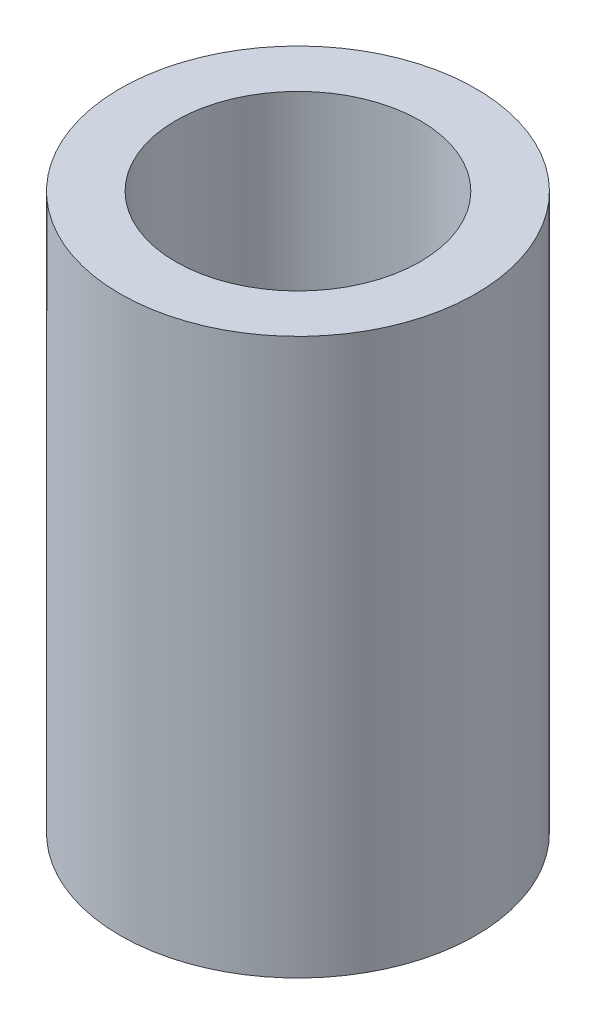
SolidWorks part; units mm, degrees
ref_plane "Płaszczyzna przednia" through (0, 0, 0) normal (0, 0, 1) x (1, 0, 0)
ref_plane "Płaszczyzna górna" through (0, 0, 0) normal (0, 1, 0) x (1, 0, 0)
ref_plane "Płaszczyzna prawa" through (0, 0, 0) normal (1, 0, 0) x (0, 0, -1)
sketch "Sketch1" plane through (0, 0, 0) normal (0, 1, 0) x (1, 0, 0)
  line L0 (-0.2998, -0.4611) -> (0.2998, 0.4611) construction
  line L1 (0.474, -0.9926) -> (-0.474, 0.9926) construction
  circle A0 centre (0, 0) radius 1.6
  circle A1 centre (0, 0) radius 1.1
  point P8 (0, 0)
  point P11 (0, 0)
  dimension "D1" = 2.2
  dimension "D2" = 3.2
extrude "Boss-Extrude1" add sketch "Sketch1" along normal blind 5
